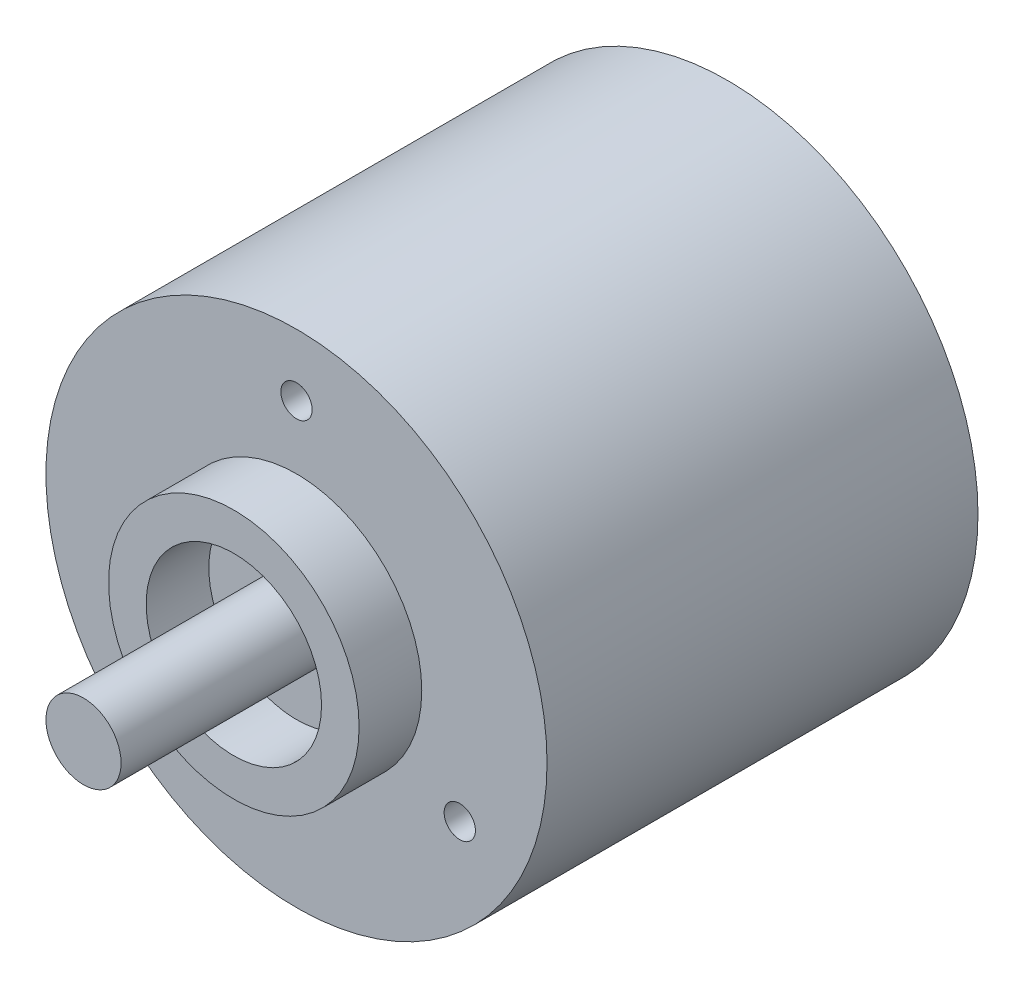
SolidWorks part; units mm, degrees
ref_plane "Plan de face" through (0, 0, 0) normal (0, 0, 1) x (1, 0, 0)
ref_plane "Plan de dessus" through (0, 0, 0) normal (0, 1, 0) x (1, 0, 0)
ref_plane "Plan de droite" through (0, 0, 0) normal (1, 0, 0) x (0, 0, -1)
sketch "Esquisse1" plane through (0, 0, 0) normal (0, 0, 1) x (1, 0, 0)
  circle A0 centre (0, 0) radius 20
  dimension "D1" = 40
extrude "Boss.-Extru.1" add sketch "Esquisse1" against normal blind 34.4
sketch "Esquisse2" plane through (0, 0, 0) normal (0, 0, 1) x (1, 0, 0)
  circle A0 centre (0, 0) radius 10
  circle A1 centre (0, 0) radius 7
  dimension "D1" = 20
  dimension "D2" = 3
extrude "Boss.-Extru.2" add sketch "Esquisse2" along normal blind 5
sketch "Esquisse3" plane through (0, 0, 0) normal (0, 0, 1) x (1, 0, 0)
  circle A0 centre (0, 0) radius 3
  dimension "D1" = 6
extrude "Boss.-Extru.3" add sketch "Esquisse3" along normal blind 17
sketch "Esquisse4" plane through (0, 0, 0) normal (0, 0, 1) x (1, 0, 0)
  line L0 (0, -21.5832) -> (0, 21.5832) construction
  circle A0 centre (0, 15.05) radius 1.25
  circle A2 centre (13.0337, -7.525) radius 1.25
  circle A3 centre (-13.0337, -7.525) radius 1.25
  point P12 (0, 0)
  dimension "D1" = 2.5
  dimension "D2" = 15.05
  dimension "D4" = 15.05
  dimension "D3" = 3
extrude "Enlèv. mat.-Extru.1" cut sketch "Esquisse4" against normal blind 7.9
